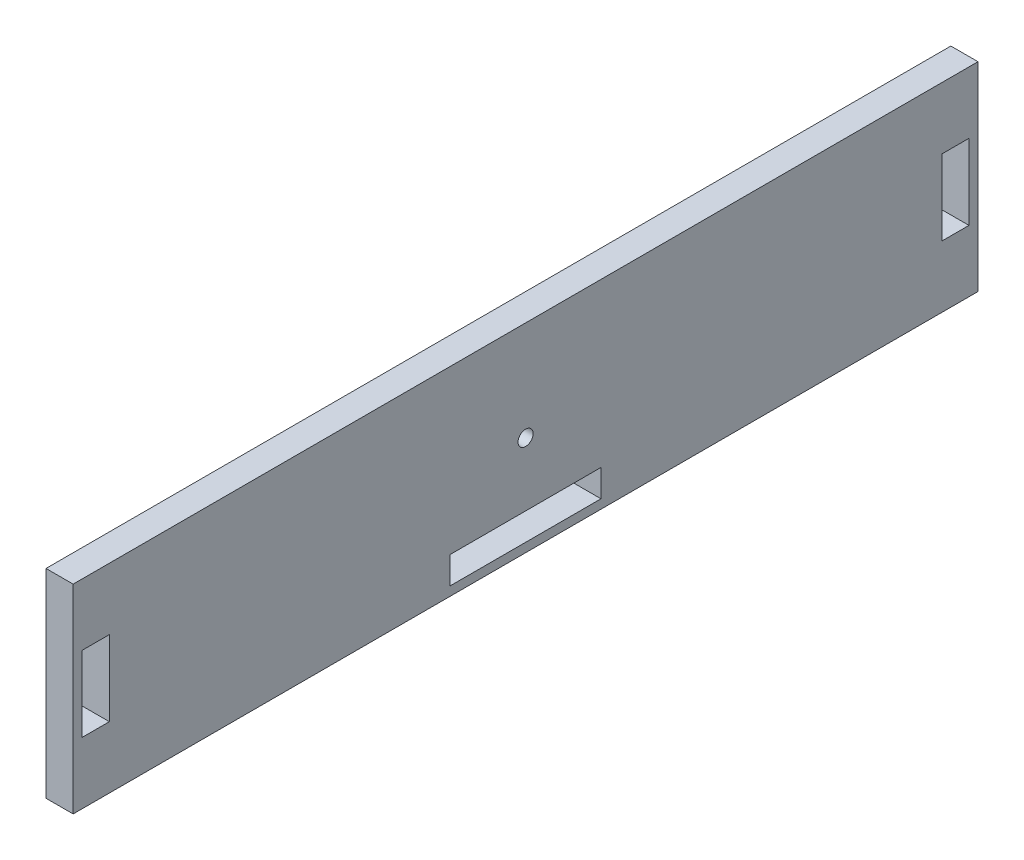
SolidWorks part; units mm, degrees
ref_plane "Front Plane" through (0, 0, 0) normal (0, 0, 1) x (1, 0, 0)
ref_plane "Top Plane" through (0, 0, 0) normal (0, 1, 0) x (1, 0, 0)
ref_plane "Right Plane" through (0, 0, 0) normal (1, 0, 0) x (0, 0, -1)
sketch "Sketch1" plane through (0, 0, 0) normal (1, 0, 0) x (0, 0, -1)
  line L0 (600, -66) -> (597.3615, -66) construction
  line L1 (0, 0) -> (600, 0)
  line L2 (0, 0) -> (0, -132)
  line L3 (0, -132) -> (600, -132)
  line L4 (600, 0) -> (600, -132)
  line L5 (300, -132) -> (300, -130.6864) construction
  circle A0 centre (300, -66) radius 0.25
  circle A1 centre (300, -66) radius 5
  dimension "D2" = 600
  dimension "D3" = 132
extrude "Boss-Extrude1" add sketch "Sketch1" along normal blind 18 contours L2 L1 L4 L3
sketch "Sketch2" plane through (18, 0, 0) normal (1, 0, 0) x (0, 0, -1)
  line L0 (300, -132) -> (300, 57.4348) construction
  line L1 (0, -132) -> (600, -132) construction
  line L2 (0, -66) -> (613.6239, -66) construction
  line L3 (0, 0) -> (0, -132) construction
  circle A0 centre (300, -48) radius 5
sketch "Sketch3" plane through (18, 0, 0) normal (1, 0, 0) x (0, 0, -1)
  line L0 (600, -66) -> (-78.6996, -66) construction
  line L1 (600, 0) -> (600, -132) construction
  line L2 (300, -132) -> (300, 57.4348) construction
  circle A2 centre (300, -66) radius 5
extrude "Cut-Extrude2" cut sketch "Sketch3" against normal blind 584
sketch "Sketch4" plane through (18, 0, 0) normal (1, 0, 0) x (0, 0, -1)
  line L0 (0, -66) -> (613.6239, -66) construction
  line L1 (576, -41) -> (594, -41)
  line L2 (576, -41) -> (576, -91)
  line L3 (576, -91) -> (594, -91)
  line L4 (594, -41) -> (594, -91)
  line L5 (576, -41) -> (594, -91) construction
  line L6 (576, -91) -> (594, -41) construction
  line L7 (600, 0) -> (600, -132) construction
  line L8 (599.1576, -66) -> (-16.1603, -66) construction
  line L9 (300, 0) -> (300, -150.3193) construction
  line L10 (0, 0) -> (600, 0) construction
  line L11 (24, -91) -> (6, -91)
  line L12 (24, -41) -> (24, -91)
  line L13 (24, -41) -> (6, -41)
  line L14 (6, -41) -> (6, -91)
  point P0 (585, -66)
  dimension "D1" = 6
  dimension "D2" = 18
  dimension "D3" = 50
extrude "Cut-Extrude4" cut sketch "Sketch4" against normal through all
sketch "Sketch5" plane through (18, 0, 0) normal (1, 0, 0) x (0, 0, -1)
  line L0 (300, -132) -> (300, 57.4348) construction
  line L1 (250, -108) -> (350, -108)
  line L2 (250, -108) -> (250, -126)
  line L3 (250, -126) -> (350, -126)
  line L4 (350, -108) -> (350, -126)
  line L5 (250, -108) -> (350, -126) construction
  line L6 (250, -126) -> (350, -108) construction
  line L7 (0, -132) -> (600, -132) construction
  point P0 (300, -117)
  dimension "D1" = 6
  dimension "D2" = 18
  dimension "D3" = 100
extrude "Cut-Extrude5" cut sketch "Sketch5" against normal through all
